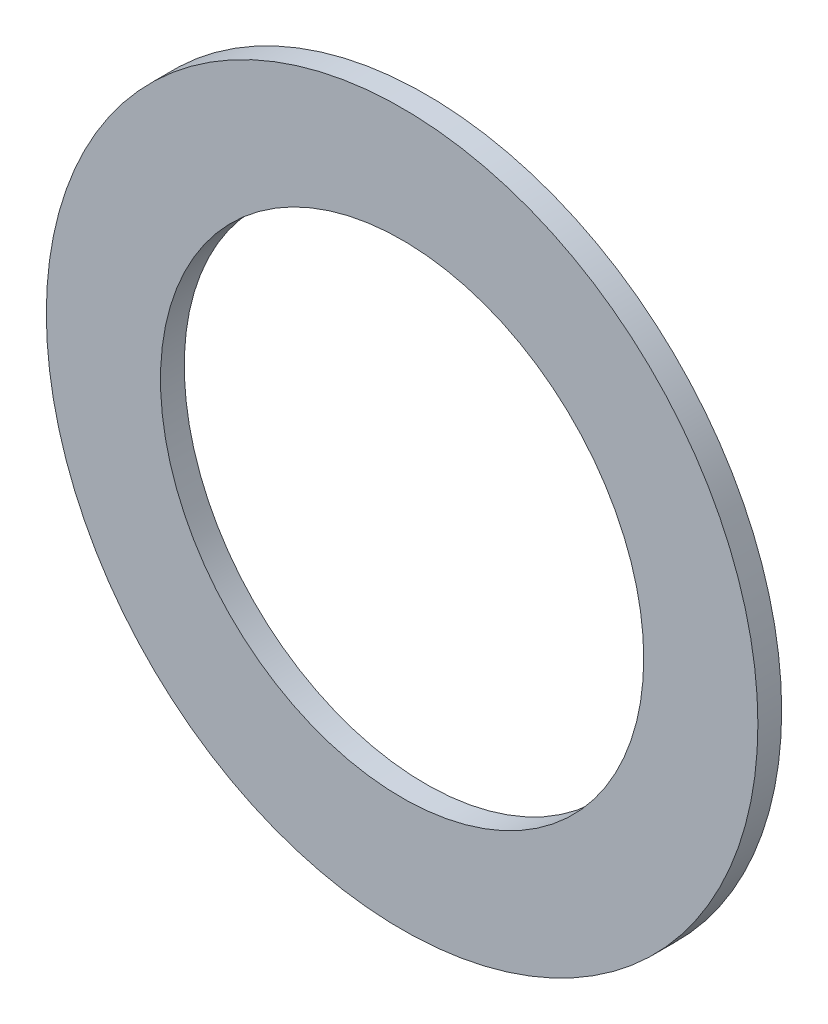
SolidWorks part; units mm, degrees
material "1023 Carbon Steel Sheet (SS)"
ref_plane "Front Plane" through (0, 0, 0) normal (0, 0, 1) x (1, 0, 0)
ref_plane "Top Plane" through (0, 0, 0) normal (0, 1, 0) x (1, 0, 0)
ref_plane "Right Plane" through (0, 0, 0) normal (1, 0, 0) x (0, 0, -1)
sketch "Sketch1" plane through (0, 0, 0) normal (0, 0, 1) x (1, 0, 0)
  circle A0 centre (0, 0) radius 23.749
  dimension "D1" = 47.498
extrude "Boss-Extrude1" add sketch "Sketch1" along normal blind 1.5875
sketch "Sketch2" plane through (0, 0, 1.5875) normal (0, 0, 1) x (1, 0, 0)
  circle A0 centre (0, 0) radius 16.129
  dimension "D1" = 32.258
extrude "Cut-Extrude1" cut sketch "Sketch2" against normal through all
